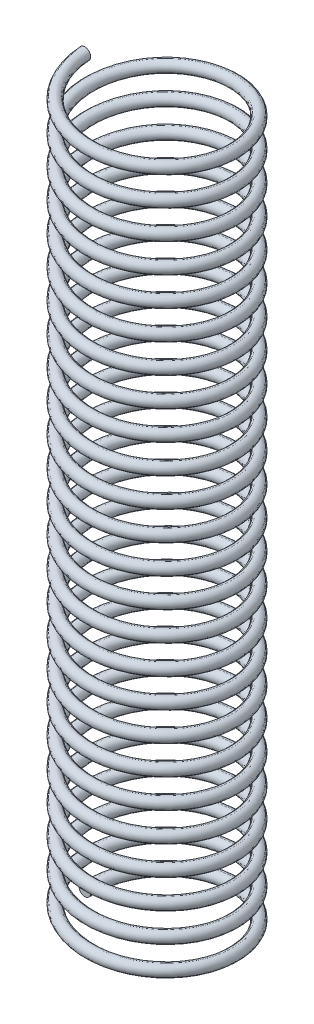
SolidWorks part; units mm, degrees
ref_plane "Front Plane" through (0, 0, 0) normal (0, 0, 1) x (1, 0, 0)
ref_plane "Top Plane" through (0, 0, 0) normal (0, 1, 0) x (1, 0, 0)
ref_plane "Right Plane" through (0, 0, 0) normal (1, 0, 0) x (0, 0, -1)
sketch "Sketch1" plane through (0, 0, 0) normal (0, 1, 0) x (1, 0, 0)
  circle A0 centre (0, 0) radius 1.5875
  dimension "D1" = 3.175
curve "Helix/Spiral1" pitch 0.6376 height 15.9408 turns 25
sketch "Sketch13" plane through (0, 0, 0) normal (0, 0, 1) x (1, 0, 0)
  circle A0 centre (-1.5875, 0) radius 0.127
  spline S0 degree 3 poles (-1.5875, 0) (-1.5875, 0.0132) (-1.5048, 0.0399) (-1.1518, 0.0797) (-0.4472, 0.1328) (0.4472, 0.186) (1.1518, 0.2391) (1.5048, 0.279) (1.6288, 0.3188) (1.5048, 0.3587) (1.1518, 0.3985) (0.4472, 0.4517) (-0.4472, 0.5048) (-1.1518, 0.5579) (-1.5048, 0.5978) (-1.6288, 0.6376) (-1.5048, 0.6775) (-1.1518, 0.7173) (-0.4472, 0.7705) (0.4472, 0.8236) (1.1518, 0.8767) (1.5048, 0.9166) (1.6288, 0.9565) (1.5048, 0.9963) (1.1518, 1.0362) (0.4472, 1.0893) (-0.4472, 1.1424) (-1.1518, 1.1956) (-1.5048, 1.2354) (-1.6288, 1.2753) (-1.5048, 1.3151) (-1.1518, 1.355) (-0.4472, 1.4081) (0.4472, 1.4612) (1.1518, 1.5144) (1.5048, 1.5542) (1.6288, 1.5941) (1.5048, 1.6339) (1.1518, 1.6738) (0.4472, 1.7269) (-0.4472, 1.7801) (-1.1518, 1.8332) (-1.5048, 1.873) (-1.6288, 1.9129) (-1.5048, 1.9528) (-1.1518, 1.9926) (-0.4472, 2.0457) (0.4472, 2.0989) (1.1518, 2.152) (1.5048, 2.1919) (1.6288, 2.2317) (1.5048, 2.2716) (1.1518, 2.3114) (0.4472, 2.3646) (-0.4472, 2.4177) (-1.1518, 2.4708) (-1.5048, 2.5107) (-1.6288, 2.5505) (-1.5048, 2.5904) (-1.1518, 2.6302) (-0.4472, 2.6834) (0.4472, 2.7365) (1.1518, 2.7896) (1.5048, 2.8295) (1.6288, 2.8694) (1.5048, 2.9092) (1.1518, 2.9491) (0.4472, 3.0022) (-0.4472, 3.0553) (-1.1518, 3.1085) (-1.5048, 3.1483) (-1.6288, 3.1882) (-1.5048, 3.228) (-1.1518, 3.2679) (-0.4472, 3.321) (0.4472, 3.3741) (1.1518, 3.4273) (1.5048, 3.4671) (1.6288, 3.507) (1.5048, 3.5468) (1.1518, 3.5867) (0.4472, 3.6398) (-0.4472, 3.693) (-1.1518, 3.7461) (-1.5048, 3.7859) (-1.6288, 3.8258) (-1.5048, 3.8657) (-1.1518, 3.9055) (-0.4472, 3.9586) (0.4472, 4.0118) (1.1518, 4.0649) (1.5048, 4.1048) (1.6288, 4.1446) (1.5048, 4.1845) (1.1518, 4.2243) (0.4472, 4.2775) (-0.4472, 4.3306) (-1.1518, 4.3837) (-1.5048, 4.4236) (-1.6288, 4.4634) (-1.5048, 4.5033) (-1.1518, 4.5431) (-0.4472, 4.5963) (0.4472, 4.6494) (1.1518, 4.7025) (1.5048, 4.7424) (1.6288, 4.7822) (1.5048, 4.8221) (1.1518, 4.862) (0.4472, 4.9151) (-0.4472, 4.9682) (-1.1518, 5.0214) (-1.5048, 5.0612) (-1.6288, 5.1011) (-1.5048, 5.1409) (-1.1518, 5.1808) (-0.4472, 5.2339) (0.4472, 5.287) (1.1518, 5.3402) (1.5048, 5.38) (1.6288, 5.4199) (1.5048, 5.4597) (1.1518, 5.4996) (0.4472, 5.5527) (-0.4472, 5.6059) (-1.1518, 5.659) (-1.5048, 5.6988) (-1.6288, 5.7387) (-1.5048, 5.7786) (-1.1518, 5.8184) (-0.4472, 5.8715) (0.4472, 5.9247) (1.1518, 5.9778) (1.5048, 6.0177) (1.6288, 6.0575) (1.5048, 6.0974) (1.1518, 6.1372) (0.4472, 6.1904) (-0.4472, 6.2435) (-1.1518, 6.2966) (-1.5048, 6.3365) (-1.6288, 6.3763) (-1.5048, 6.4162) (-1.1518, 6.456) (-0.4472, 6.5092) (0.4472, 6.5623) (1.1518, 6.6154) (1.5048, 6.6553) (1.6288, 6.6951) (1.5048, 6.735) (1.1518, 6.7749) (0.4472, 6.828) (-0.4472, 6.8811) (-1.1518, 6.9343) (-1.5048, 6.9741) (-1.6288, 7.014) (-1.5048, 7.0538) (-1.1518, 7.0937) (-0.4472, 7.1468) (0.4472, 7.1999) (1.1518, 7.2531) (1.5048, 7.2929) (1.6288, 7.3328) (1.5048, 7.3726) (1.1518, 7.4125) (0.4472, 7.4656) (-0.4472, 7.5188) (-1.1518, 7.5719) (-1.5048, 7.6117) (-1.6288, 7.6516) (-1.5048, 7.6915) (-1.1518, 7.7313) (-0.4472, 7.7844) (0.4472, 7.8376) (1.1518, 7.8907) (1.5048, 7.9306) (1.6288, 7.9704) (1.5048, 8.0103) (1.1518, 8.0501) (0.4472, 8.1033) (-0.4472, 8.1564) (-1.1518, 8.2095) (-1.5048, 8.2494) (-1.6288, 8.2892) (-1.5048, 8.3291) (-1.1518, 8.3689) (-0.4472, 8.4221) (0.4472, 8.4752) (1.1518, 8.5283) (1.5048, 8.5682) (1.6288, 8.608) (1.5048, 8.6479) (1.1518, 8.6878) (0.4472, 8.7409) (-0.4472, 8.794) (-1.1518, 8.8472) (-1.5048, 8.887) (-1.6288, 8.9269) (-1.5048, 8.9667) (-1.1518, 9.0066) (-0.4472, 9.0597) (0.4472, 9.1128) (1.1518, 9.166) (1.5048, 9.2058) (1.6288, 9.2457) (1.5048, 9.2855) (1.1518, 9.3254) (0.4472, 9.3785) (-0.4472, 9.4317) (-1.1518, 9.4848) (-1.5048, 9.5246) (-1.6288, 9.5645) (-1.5048, 9.6044) (-1.1518, 9.6442) (-0.4472, 9.6973) (0.4472, 9.7505) (1.1518, 9.8036) (1.5048, 9.8435) (1.6288, 9.8833) (1.5048, 9.9232) (1.1518, 9.963) (0.4472, 10.0162) (-0.4472, 10.0693) (-1.1518, 10.1224) (-1.5048, 10.1623) (-1.6288, 10.2021) (-1.5048, 10.242) (-1.1518, 10.2818) (-0.4472, 10.335) (0.4472, 10.3881) (1.1518, 10.4412) (1.5048, 10.4811) (1.6288, 10.5209) (1.5048, 10.5608) (1.1518, 10.6007) (0.4472, 10.6538) (-0.4472, 10.7069) (-1.1518, 10.7601) (-1.5048, 10.7999) (-1.6288, 10.8398) (-1.5048, 10.8796) (-1.1518, 10.9195) (-0.4472, 10.9726) (0.4472, 11.0257) (1.1518, 11.0789) (1.5048, 11.1187) (1.6288, 11.1586) (1.5048, 11.1984) (1.1518, 11.2383) (0.4472, 11.2914) (-0.4472, 11.3446) (-1.1518, 11.3977) (-1.5048, 11.4375) (-1.6288, 11.4774) (-1.5048, 11.5173) (-1.1518, 11.5571) (-0.4472, 11.6102) (0.4472, 11.6634) (1.1518, 11.7165) (1.5048, 11.7564) (1.6288, 11.7962) (1.5048, 11.8361) (1.1518, 11.8759) (0.4472, 11.9291) (-0.4472, 11.9822) (-1.1518, 12.0353) (-1.5048, 12.0752) (-1.6288, 12.115) (-1.5048, 12.1549) (-1.1518, 12.1947) (-0.4472, 12.2479) (0.4472, 12.301) (1.1518, 12.3541) (1.5048, 12.394) (1.6288, 12.4338) (1.5048, 12.4737) (1.1518, 12.5136) (0.4472, 12.5667) (-0.4472, 12.6198) (-1.1518, 12.673) (-1.5048, 12.7128) (-1.6288, 12.7527) (-1.5048, 12.7925) (-1.1518, 12.8324) (-0.4472, 12.8855) (0.4472, 12.9386) (1.1518, 12.9918) (1.5048, 13.0316) (1.6288, 13.0715) (1.5048, 13.1113) (1.1518, 13.1512) (0.4472, 13.2043) (-0.4472, 13.2575) (-1.1518, 13.3106) (-1.5048, 13.3504) (-1.6288, 13.3903) (-1.5048, 13.4302) (-1.1518, 13.47) (-0.4472, 13.5231) (0.4472, 13.5763) (1.1518, 13.6294) (1.5048, 13.6693) (1.6288, 13.7091) (1.5048, 13.749) (1.1518, 13.7888) (0.4472, 13.842) (-0.4472, 13.8951) (-1.1518, 13.9482) (-1.5048, 13.9881) (-1.6288, 14.0279) (-1.5048, 14.0678) (-1.1518, 14.1076) (-0.4472, 14.1608) (0.4472, 14.2139) (1.1518, 14.267) (1.5048, 14.3069) (1.6288, 14.3467) (1.5048, 14.3866) (1.1518, 14.4265) (0.4472, 14.4796) (-0.4472, 14.5327) (-1.1518, 14.5859) (-1.5048, 14.6257) (-1.6288, 14.6656) (-1.5048, 14.7054) (-1.1518, 14.7453) (-0.4472, 14.7984) (0.4472, 14.8515) (1.1518, 14.9047) (1.5048, 14.9445) (1.6288, 14.9844) (1.5048, 15.0242) (1.1518, 15.0641) (0.4472, 15.1172) (-0.4472, 15.1704) (-1.1518, 15.2235) (-1.5048, 15.2633) (-1.6288, 15.3032) (-1.5048, 15.3431) (-1.1518, 15.3829) (-0.4472, 15.436) (0.4472, 15.4892) (1.1518, 15.5423) (1.5048, 15.5822) (1.6288, 15.622) (1.5048, 15.6619) (1.1518, 15.7017) (0.4472, 15.7549) (-0.4472, 15.808) (-1.1518, 15.8611) (-1.5048, 15.9009) (-1.5875, 15.9276) (-1.5875, 15.9408) knots 0 0 0 0 0.0025 0.005 0.0075 0.0125 0.015 0.0175 0.02 0.0225 0.025 0.0275 0.0325 0.035 0.0375 0.04 0.0425 0.045 0.0475 0.0525 0.055 0.0575 0.06 0.0625 0.065 0.0675 0.0725 0.075 0.0775 0.08 0.0825 0.085 0.0875 0.0925 0.095 0.0975 0.1 0.1025 0.105 0.1075 0.1125 0.115 0.1175 0.12 0.1225 0.125 0.1275 0.1325 0.135 0.1375 0.14 0.1425 0.145 0.1475 0.1525 0.155 0.1575 0.16 0.1625 0.165 0.1675 0.1725 0.175 0.1775 0.18 0.1825 0.185 0.1875 0.1925 0.195 0.1975 0.2 0.2025 0.205 0.2075 0.2125 0.215 0.2175 0.22 0.2225 0.225 0.2275 0.2325 0.235 0.2375 0.24 0.2425 0.245 0.2475 0.2525 0.255 0.2575 0.26 0.2625 0.265 0.2675 0.2725 0.275 0.2775 0.28 0.2825 0.285 0.2875 0.2925 0.295 0.2975 0.3 0.3025 0.305 0.3075 0.3125 0.315 0.3175 0.32 0.3225 0.325 0.3275 0.3325 0.335 0.3375 0.34 0.3425 0.345 0.3475 0.3525 0.355 0.3575 0.36 0.3625 0.365 0.3675 0.3725 0.375 0.3775 0.38 0.3825 0.385 0.3875 0.3925 0.395 0.3975 0.4 0.4025 0.405 0.4075 0.4125 0.415 0.4175 0.42 0.4225 0.425 0.4275 0.4325 0.435 0.4375 0.44 0.4425 0.445 0.4475 0.4525 0.455 0.4575 0.46 0.4625 0.465 0.4675 0.4725 0.475 0.4775 0.48 0.4825 0.485 0.4875 0.4925 0.495 0.4975 0.5 0.5025 0.505 0.5075 0.5125 0.515 0.5175 0.52 0.5225 0.525 0.5275 0.5325 0.535 0.5375 0.54 0.5425 0.545 0.5475 0.5525 0.555 0.5575 0.56 0.5625 0.565 0.5675 0.5725 0.575 0.5775 0.58 0.5825 0.585 0.5875 0.5925 0.595 0.5975 0.6 0.6025 0.605 0.6075 0.6125 0.615 0.6175 0.62 0.6225 0.625 0.6275 0.6325 0.635 0.6375 0.64 0.6425 0.645 0.6475 0.6525 0.655 0.6575 0.66 0.6625 0.665 0.6675 0.6725 0.675 0.6775 0.68 0.6825 0.685 0.6875 0.6925 0.695 0.6975 0.7 0.7025 0.705 0.7075 0.7125 0.715 0.7175 0.72 0.7225 0.725 0.7275 0.7325 0.735 0.7375 0.74 0.7425 0.745 0.7475 0.7525 0.755 0.7575 0.76 0.7625 0.765 0.7675 0.7725 0.775 0.7775 0.78 0.7825 0.785 0.7875 0.7925 0.795 0.7975 0.8 0.8025 0.805 0.8075 0.8125 0.815 0.8175 0.82 0.8225 0.825 0.8275 0.8325 0.835 0.8375 0.84 0.8425 0.845 0.8475 0.8525 0.855 0.8575 0.86 0.8625 0.865 0.8675 0.8725 0.875 0.8775 0.88 0.8825 0.885 0.8875 0.8925 0.895 0.8975 0.9 0.9025 0.905 0.9075 0.9125 0.915 0.9175 0.92 0.9225 0.925 0.9275 0.9325 0.935 0.9375 0.94 0.9425 0.945 0.9475 0.9525 0.955 0.9575 0.96 0.9625 0.965 0.9675 0.9725 0.975 0.9775 0.98 0.9825 0.985 0.9875 0.9925 0.995 0.9975 1 1 1 1 construction
  dimension "D1" = 0.254
sweep "Sweep2" add profiles "Sketch13" path "Helix/Spiral1"
